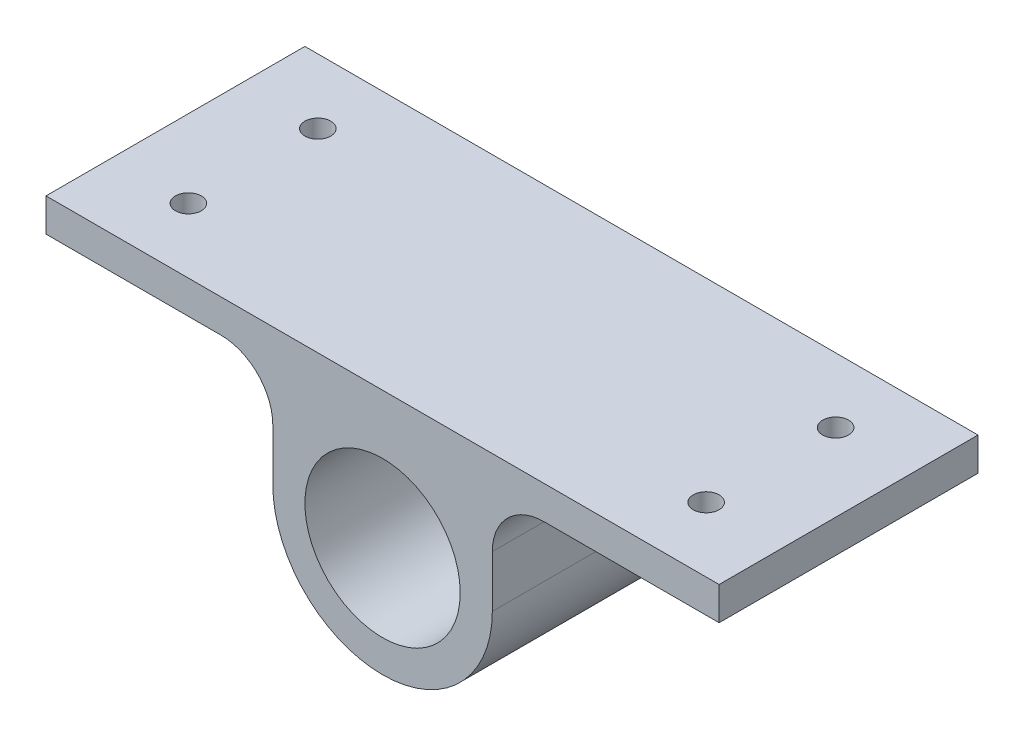
SolidWorks part; units mm, degrees
ref_plane "Front Plane" through (0, 0, 0) normal (0, 0, 1) x (1, 0, 0)
ref_plane "Top Plane" through (0, 0, 0) normal (0, 1, 0) x (1, 0, 0)
ref_plane "Right Plane" through (0, 0, 0) normal (1, 0, 0) x (0, 0, -1)
sketch "Sketch1" plane through (0, 0, 0) normal (0, 0, 1) x (1, 0, 0)
  line L0 (0, 260.6352) -> (0, -260.6352) construction
  line L1 (-235.4602, 0) -> (235.4602, 0) construction
  line L2 (-106, 0) -> (-106, 50)
  line L3 (-156, 100) -> (-325, 100)
  line L4 (-325, 100) -> (-325, 132)
  line L5 (-325, 132) -> (325, 132)
  line L6 (325, 132) -> (325, 100)
  line L7 (325, 100) -> (156, 100)
  line L8 (106, 50) -> (106, 0)
  circle A0 centre (0, 0) radius 75
  arc A1 (-106, 0) -> (106, 0) centre (0, 0) ccw
  arc A2 (-106, 50) -> (-156, 100) centre (-156, 50) ccw
  arc A3 (156, 100) -> (106, 50) centre (156, 50) ccw
  point P3 (0, 0)
  point P7 (0, 0)
  point P9 (0, 0)
  point P15 (325, 97.6196)
  dimension "D1" = 150
  dimension "D2" = 212
  dimension "D6" = 50
  dimension "D7" = 50
  dimension "D3" = 132
  dimension "D4" = 32
  dimension "D5" = 325
  dimension "D8" = 325
extrude "Boss-Extrude1" add sketch "Sketch1" along normal blind 250
sketch "Sketch2" plane through (0, 132, 0) normal (0, 1, 0) x (1, 0, 0)
  line L0 (0, 0) -> (0, -250) construction
  line L1 (325, -250) -> (-325, -250) construction
  line L2 (325, 0) -> (-325, 0) construction
  line L3 (-325, -250) -> (-325, 0) construction
  line L4 (325, -250) -> (325, 0) construction
  circle A0 centre (-250, -62.5) radius 12.5
  circle A1 centre (-250, -187.5) radius 12.5
  circle A2 centre (250, -187.5) radius 12.5
  circle A3 centre (250, -62.5) radius 12.5
  point P17 (0, 0)
  point P20 (0, 0)
  dimension "D1" = 25
  dimension "D2" = 25
  dimension "D3" = 25
  dimension "D4" = 25
  dimension "D8" = 500
  dimension "D10" = 62.5
  dimension "D11" = 125
  dimension "D5" = 62.5
  dimension "D6" = 125
  dimension "D7" = 75
  dimension "D9" = 75
extrude "Cut-Extrude1" cut sketch "Sketch2" against normal blind 250
